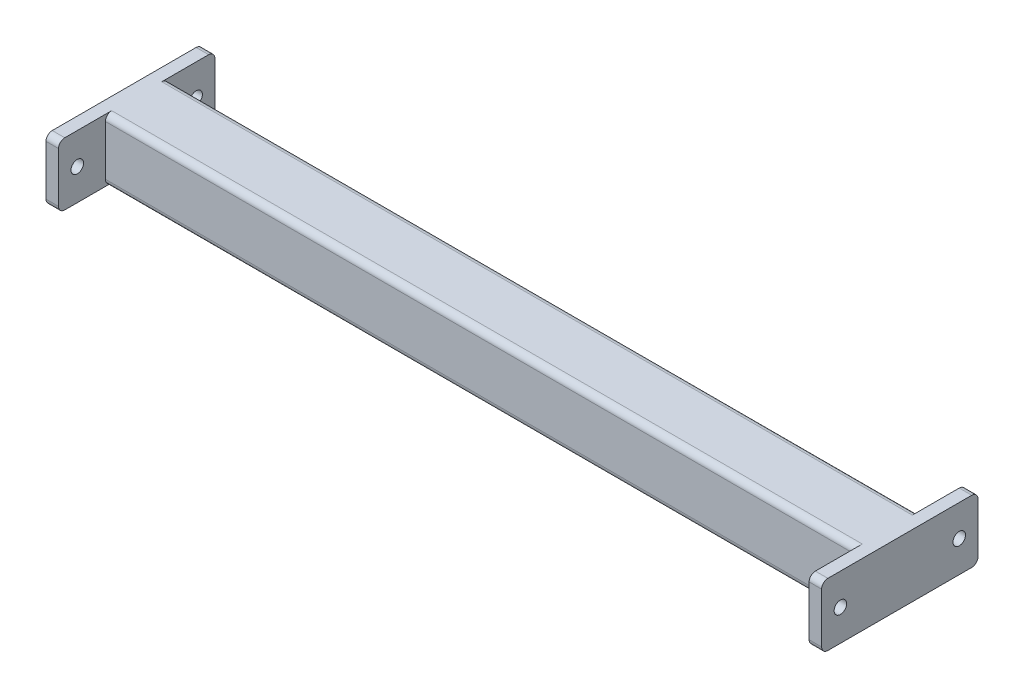
SolidWorks part; units mm, degrees
ref_plane "Front Plane" through (0, 0, 0) normal (0, 0, 1) x (1, 0, 0)
ref_plane "Top Plane" through (0, 0, 0) normal (0, 1, 0) x (1, 0, 0)
ref_plane "Right Plane" through (0, 0, 0) normal (1, 0, 0) x (0, 0, -1)
sketch "Sketch1" plane through (0, 0, 0) normal (1, 0, 0) x (0, 0, -1)
  line L0 (-20, 23) -> (20, 23)
  line L1 (-20, 25) -> (20, 25)
  line L2 (-25, 20) -> (-25, -20)
  line L3 (-20, -25) -> (20, -25)
  line L4 (25, 20) -> (25, -20)
  line L5 (-25, 25) -> (25, -25) construction
  line L6 (-25, -25) -> (25, 25) construction
  line L7 (23, 20) -> (23, -20)
  line L8 (-20, -23) -> (20, -23)
  line L9 (-23, 20) -> (-23, -20)
  arc A0 (20, 25) -> (25, 20) centre (20, 20) cw
  arc A1 (20, -25) -> (25, -20) centre (20, -20) ccw
  arc A2 (-25, -20) -> (-20, -25) centre (-20, -20) ccw
  arc A3 (-20, 25) -> (-25, 20) centre (-20, 20) ccw
  arc A4 (20, 23) -> (23, 20) centre (20, 20) cw
  arc A5 (20, -23) -> (23, -20) centre (20, -20) ccw
  arc A6 (-23, -20) -> (-20, -23) centre (-20, -20) ccw
  arc A7 (-20, 23) -> (-23, 20) centre (-20, 20) ccw
  point P0 (0, 0)
  dimension "D2" = 5
  dimension "D1" = 50
  dimension "D3" = 2
extrude "Boss-Extrude1" add sketch "Sketch1" along normal mid plane 600
sketch "Sketch2" plane through (300, 0, 0) normal (1, 0, 0) x (0, 0, -1)
  line L0 (-57.5, 25) -> (57.5, 25)
  line L1 (20, 25) -> (-20, 25) construction
  line L2 (62.5, 20) -> (62.5, -20)
  line L3 (57.5, -25) -> (-57.5, -25)
  line L4 (-20, -25) -> (20, -25) construction
  line L5 (0, 0) -> (0, 25) construction
  line L6 (-62.5, 20) -> (-62.5, -20)
  arc A0 (62.5, -20) -> (57.5, -25) centre (57.5, -20) cw
  arc A1 (57.5, 25) -> (62.5, 20) centre (57.5, 20) cw
  arc A2 (-57.5, 25) -> (-62.5, 20) centre (-57.5, 20) ccw
  arc A3 (-62.5, -20) -> (-57.5, -25) centre (-57.5, -20) ccw
  point P21 (0, -25)
  dimension "D2" = 5
  dimension "D1" = 125
extrude "Boss-Extrude2" add sketch "Sketch2" along normal blind 10
mirror "Mirror1" about plane through (0, 0, 0) normal (1, 0, 0) of "Boss-Extrude2"
sketch "Sketch3" plane through (310, 0, 0) normal (1, 0, 0) x (0, 0, -1)
  line L0 (-62.5, 20) -> (-62.5, -20) construction
  line L1 (0, 0) -> (0, 40.9387) construction
  circle A0 centre (-47.5, 0) radius 5
  circle A1 centre (47.5, 0) radius 5
  point P10 (-62.5, 0)
  dimension "D2" = 10
  dimension "D1" = 20
extrude "Cut-Extrude1" cut sketch "Sketch3" against normal through all
